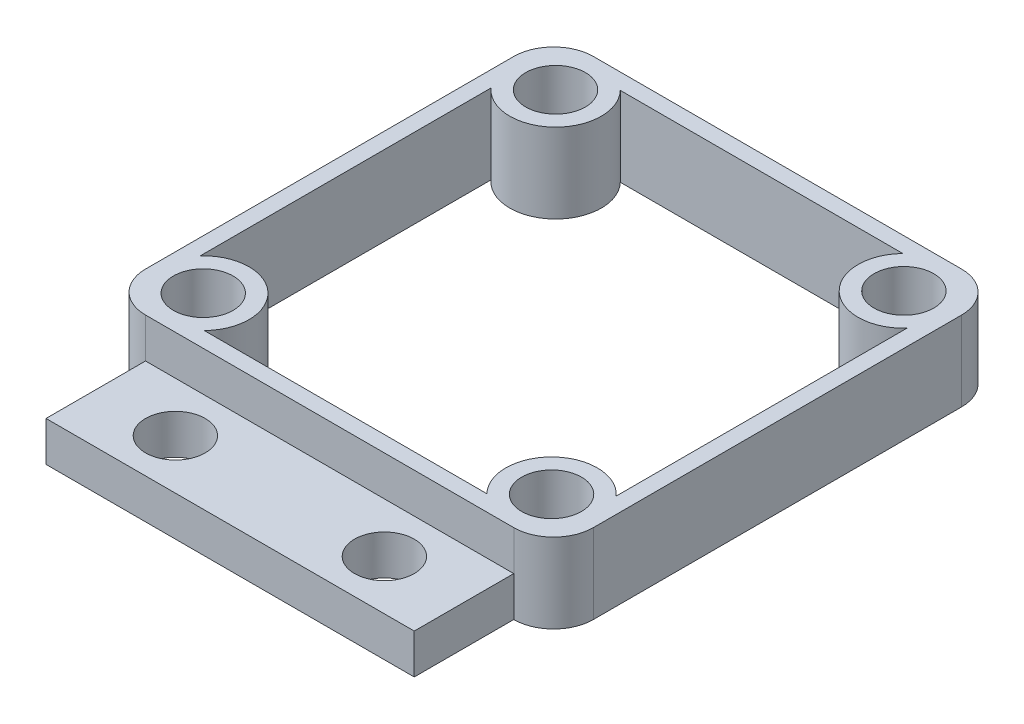
SolidWorks part; units mm, degrees
ref_plane "Front Plane" through (0, 0, 0) normal (0, 0, 1) x (1, 0, 0)
ref_plane "Top Plane" through (0, 0, 0) normal (0, 1, 0) x (1, 0, 0)
ref_plane "Right Plane" through (0, 0, 0) normal (1, 0, 0) x (0, 0, -1)
sketch "Sketch1" plane through (0, 0, 0) normal (0, 1, 0) x (1, 0, 0)
  line L0 (0, 11.25) -> (0, -11.25) construction
  line L1 (-9.25, 11.25) -> (9.25, 11.25)
  line L2 (-11.25, 9.25) -> (-11.25, -9.25)
  line L3 (-9.25, -11.25) -> (9.25, -11.25)
  line L4 (11.25, 9.25) -> (11.25, -9.25)
  line L5 (-11.25, 11.25) -> (11.25, -11.25) construction
  line L6 (-11.25, -11.25) -> (11.25, 11.25) construction
  line L7 (11.25, 0) -> (-11.2452, 0) construction
  line L8 (-7.0977, 10.45) -> (7.0977, 10.45)
  line L9 (10.45, 7.3008) -> (10.45, -7.3008)
  line L10 (-7.0977, -10.45) -> (7.0977, -10.45)
  line L11 (-10.45, 7.3008) -> (-10.45, -7.3008)
  line L12 (10.45, 9.25) -> (10.45, -9.25) construction
  line L13 (-9.25, -10.45) -> (9.25, -10.45) construction
  line L14 (-10.45, 9.25) -> (-10.45, -9.25) construction
  line L15 (-9.25, 10.45) -> (9.25, 10.45) construction
  arc A0 (9.25, 11.25) -> (11.25, 9.25) centre (9.25, 9.25) cw
  arc A1 (9.25, -11.25) -> (11.25, -9.25) centre (9.25, -9.25) ccw
  arc A2 (-11.25, -9.25) -> (-9.25, -11.25) centre (-9.25, -9.25) ccw
  arc A3 (-9.25, 11.25) -> (-11.25, 9.25) centre (-9.25, 9.25) ccw
  circle A4 centre (8.75, 8.85) radius 1.5
  circle A5 centre (8.75, -8.85) radius 1.5
  circle A6 centre (-8.75, 8.85) radius 1.5
  circle A7 centre (-8.75, -8.85) radius 1.5
  arc A8 (7.0977, 10.45) -> (10.45, 7.3008) centre (8.75, 8.85) ccw
  arc A9 (-7.0977, 10.45) -> (-10.45, 7.3008) centre (-8.75, 8.85) cw
  arc A10 (7.0977, -10.45) -> (10.45, -7.3008) centre (8.75, -8.85) cw
  arc A11 (-7.0977, -10.45) -> (-10.45, -7.3008) centre (-8.75, -8.85) ccw
  arc A16 (9.25, -10.45) -> (10.45, -9.25) centre (9.25, -9.25) ccw construction
  circle A17 centre (8.75, -8.85) radius 2.3 construction
  circle A18 centre (-8.75, -8.85) radius 2.3 construction
  arc A19 (-10.45, -9.25) -> (-9.25, -10.45) centre (-9.25, -9.25) ccw construction
  circle A20 centre (8.75, 8.85) radius 2.3 construction
  arc A21 (9.25, 10.45) -> (10.45, 9.25) centre (9.25, 9.25) cw construction
  circle A22 centre (-8.75, 8.85) radius 2.3 construction
  arc A23 (-9.25, 10.45) -> (-10.45, 9.25) centre (-9.25, 9.25) ccw construction
  point P0 (0, 0)
  point P58 (-7.1752, 7.1737)
  dimension "D3" = 2
  dimension "D4" = 2
  dimension "D5" = 3
  dimension "D1" = 22.5
  dimension "D2" = 22.5
  dimension "D6" = 2.5
  dimension "D7" = 2.4
  dimension "D8" = 8.85
  dimension "D11" = 2.3
  dimension "D9" = 0.8
  dimension "D10" = 0.8
extrude "Boss-Extrude1" add sketch "Sketch1" along normal blind 4
sketch "Sketch2" plane through (0, 0, 11.25) normal (0, 0, 1) x (1, 0, 0)
  line L0 (9.25, 2) -> (-9.25, 2) construction
  line L1 (9.25, 4) -> (9.25, 0) construction
  line L2 (-9.25, 4) -> (-9.25, 0) construction
  line M2 (-9.25, 0) -> (9.25, 0)
  line M3 (9.25, 0) -> (9.25, 4)
  line M5 (-9.25, 4) -> (-9.25, 0)
extrude "Boss-Extrude2" add sketch "Sketch2" along normal blind 5 contours L0 M3 M5 M2
sketch "Sketch3" plane through (0, 2, 0) normal (0, 1, 0) x (1, 0, 0)
  line L0 (9.25, -11.25) -> (-9.25, -11.25) construction
  line L1 (9.25, -16.25) -> (9.25, -11.25) construction
  line L2 (0, -11.3939) -> (0, -16.25) construction
  line L3 (9.25, -16.25) -> (-9.25, -16.25) construction
  circle A0 centre (5.25, -13.75) radius 1.5
  circle A1 centre (-5.25, -13.75) radius 1.5
  dimension "D3" = 3
  dimension "D1" = 2.5
  dimension "D2" = 4
extrude "Cut-Extrude1" cut sketch "Sketch3" against normal blind 5
